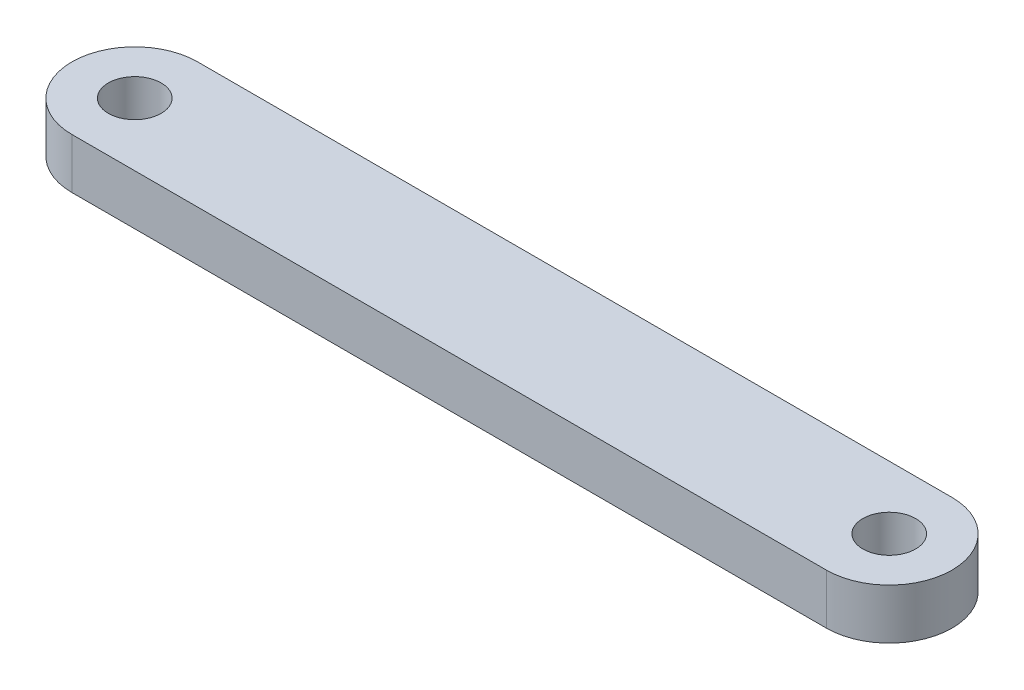
SolidWorks part; units mm, degrees
ref_plane "Front Plane" through (0, 0, 0) normal (0, 0, 1) x (1, 0, 0)
ref_plane "Top Plane" through (0, 0, 0) normal (0, 1, 0) x (1, 0, 0)
ref_plane "Right Plane" through (0, 0, 0) normal (1, 0, 0) x (0, 0, -1)
sketch "Sketch1" plane through (0, 0, 0) normal (0, 1, 0) x (1, 0, 0)
  line L0 (0, 0) -> (30, 0) construction
  line L1 (0, 2.5) -> (30, 2.5)
  line L2 (0, -2.5) -> (30, -2.5)
  arc A0 (0, 2.5) -> (0, -2.5) centre (0, 0) ccw
  arc A1 (30, -2.5) -> (30, 2.5) centre (30, 0) ccw
  circle A2 centre (0, 0) radius 1.05
  circle A3 centre (30, 0) radius 1.05
  point P3 (15, 0)
  dimension "D1" = 2.5
  dimension "D3" = 2.1
  dimension "D4" = 2.1
  dimension "D2" = 30
extrude "Boss-Extrude1" add sketch "Sketch1" along normal blind 2
